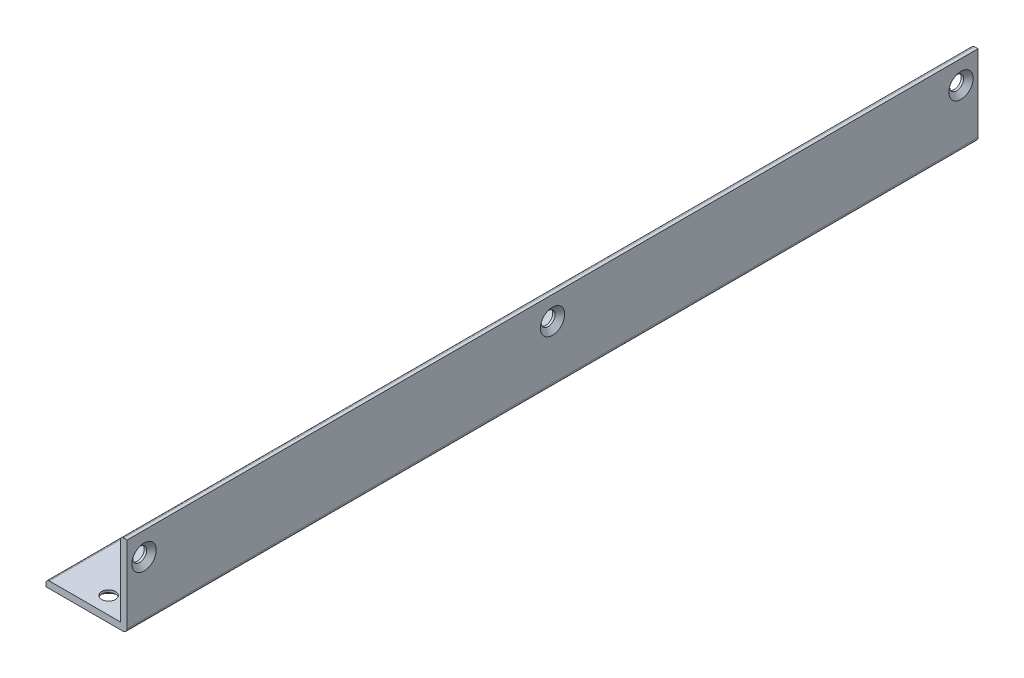
SolidWorks part; units mm, degrees
material "6061-T6 (SS)"
ref_plane "Front Plane" through (0, 0, 0) normal (0, 0, 1) x (1, 0, 0)
ref_plane "Top Plane" through (0, 0, 0) normal (0, 1, 0) x (1, 0, 0)
ref_plane "Right Plane" through (0, 0, 0) normal (1, 0, 0) x (0, 0, -1)
sketch "Sketch2" plane through (0, 0, 0) normal (0, 0, 1) x (1, 0, 0)
  line L0 (-9.525, 0) -> (9.525, 0)
  line L1 (9.525, 0) -> (9.525, 19.05)
  line L2 (9.525, 19.05) -> (7.9375, 19.05) construction
  line L3 (7.9375, 18.2563) -> (7.9375, 2.3812)
  line L4 (7.1438, 1.5875) -> (-8.7313, 1.5875)
  line L5 (-9.525, 0) -> (-9.525, 1.5875) construction
  line L6 (8.7313, 19.05) -> (9.525, 19.05)
  line L7 (-9.525, 0.7937) -> (-9.525, 0)
  arc A0 (7.9375, 18.2563) -> (8.7313, 19.05) centre (8.7313, 18.2563) cw
  arc A1 (-9.525, 0.7937) -> (-8.7313, 1.5875) centre (-8.7313, 0.7937) cw
  arc A2 (7.9375, 2.3812) -> (7.1438, 1.5875) centre (7.1438, 2.3812) cw
  dimension "Vert" = 19.05
  dimension "Horz" = 19.05
  dimension "Thickness" = 1.5875
extrude "Boss-Extrude1" add sketch "Sketch2" along normal mid plane 200
ref_plane "Contact Plane 1" through (0, 1.5875, 0) normal (0, 1, 0) x (1, 0, 0)
ref_plane "Contact Plane 2" through (7.9375, 0, 0) normal (-1, 0, 0) x (0, 0, 1)
sketch "Sketch6" plane through (0, 0, 0) normal (0, -1, 0) x (1, 0, 0)
  line L0 (9.525, 96) -> (1.185, 96) construction
  line L1 (9.525, 100) -> (9.525, -100) construction
  line L2 (-9.525, 100) -> (9.525, 100) construction
  line L3 (-9.525, -100) -> (9.525, -100) construction
  point P7 (1.185, 96)
  point P11 (0.275, -96)
  dimension "D1" = 4
  dimension "D2" = 8.34
  dimension "D3" = 4
  dimension "D4" = 9.25
hole_wizard "CSK for #4 Flat Head Machine Screw (100)1" positions "Sketch7" profile "Sketch8" countersink size "#4" standard "ANSI Inch" end condition through all
sketch "Sketch7" plane through (0, 0, 0) normal (0, -1, 0) x (-1, 0, 0)
  point P0 (-1.185, -96)
  point P3 (-0.275, 96)
sketch "Sketch8" plane through (1.185, 0, 96) normal (1, 0, 0) x (0, 0, -1)
  line L0 (0, 0) -> (0, 19.05)
  line L1 (0, 19.05) -> (1.6319, 19.05)
  line L2 (1.6319, 19.05) -> (1.6319, 1.0284)
  line L3 (1.6319, 1.0284) -> (2.8575, 0)
  line L5 (2.8575, 0) -> (0, 0)
  line L6 (-1.6319, 1.0284) -> (-2.8575, 0) construction
  line L11 (0, -6.35) -> (0, 107.95) construction
  dimension "Thru Hole Dia." = 3.2639
  dimension "Thru Hole Depth" = 19.05
  dimension "Near C'Sink Dia." = 5.715
  dimension "Near C'Sink Angle" = 100
sketch "Sketch9" plane through (9.525, 0, 0) normal (1, 0, 0) x (0, 0, -1)
  line L0 (-96, 0) -> (-96, 13.5875) construction
  line L1 (0, 0) -> (0, 19.05) construction
  line L2 (-100, 0) -> (100, 0) construction
  line L3 (-100, 19.05) -> (100, 19.05) construction
  point P4 (-96, 13.5875)
  point P10 (96, 13.5875)
  dimension "D1" = 13.5875
hole_wizard "CSK for #4 Flat Head Machine Screw (100)2" positions "Sketch10" profile "Sketch11" countersink size "#4" standard "ANSI Inch" end condition through all
sketch "Sketch10" plane through (9.525, 0, 0) normal (1, 0, 0) x (0, 0, -1)
  point P0 (-96, 13.5875)
  point P3 (96, 13.5875)
sketch "Sketch11" plane through (9.525, 13.5875, 96) normal (0, 1, 0) x (0, 0, -1)
  line L0 (0, 0) -> (0, 19.05)
  line L1 (0, 19.05) -> (1.6319, 19.05)
  line L2 (1.6319, 19.05) -> (1.6319, 1.0284)
  line L3 (1.6319, 1.0284) -> (2.8575, 0)
  line L5 (2.8575, 0) -> (0, 0)
  line L6 (-1.6319, 1.0284) -> (-2.8575, 0) construction
  line L11 (0, -6.35) -> (0, 107.95) construction
  dimension "Thru Hole Dia." = 3.2639
  dimension "Thru Hole Depth" = 19.05
  dimension "Near C'Sink Dia." = 5.715
  dimension "Near C'Sink Angle" = 100
fillet "Fillet1" radius 1 1 edges at (9.525, 0, 0)
sketch "Sketch12" plane through (0, 0, 0) normal (0, -1, 0) x (1, 0, 0)
  line L0 (0.275, -96) -> (0.275, -100) construction
  line L2 (-9.525, -100) -> (8.525, -100) construction
  line L3 (0.275, -100) -> (0.275, 0) construction
  point P8 (0.275, 0)
  dimension "D1" = 100
hole_wizard "CSK for #4 Flat Head Machine Screw (100)3" positions "Sketch15" profile "Sketch16" countersink size "#4" standard "ANSI Inch" end condition through all
sketch "Sketch15" plane through (0, 0, 0) normal (0, -1, 0) x (-1, 0, 0)
  point P0 (-0.275, 0)
sketch "Sketch16" plane through (0.275, 0, 0) normal (1, 0, 0) x (0, 0, -1)
  line L0 (0, 0) -> (0, 19.05)
  line L1 (0, 19.05) -> (1.6319, 19.05)
  line L2 (1.6319, 19.05) -> (1.6319, 1.0284)
  line L3 (1.6319, 1.0284) -> (2.8575, 0)
  line L5 (2.8575, 0) -> (0, 0)
  line L6 (-1.6319, 1.0284) -> (-2.8575, 0) construction
  line L11 (0, -6.35) -> (0, 107.95) construction
  dimension "Thru Hole Dia." = 3.2639
  dimension "Thru Hole Depth" = 19.05
  dimension "Near C'Sink Dia." = 5.715
  dimension "Near C'Sink Angle" = 100
sketch "Sketch17" plane through (9.525, 0, 0) normal (1, 0, 0) x (0, 0, -1)
  line L0 (96, 13.5875) -> (100, 13.5875) construction
  line L1 (100, 1) -> (100, 19.05) construction
  line L2 (100, 13.5875) -> (0, 13.5875) construction
  point P7 (0, 13.5875)
  dimension "D1" = 100
hole_wizard "CSK for #4 Flat Head Machine Screw (100)4" positions "Sketch18" profile "Sketch19" countersink size "#4" standard "ANSI Inch" end condition through all
sketch "Sketch18" plane through (9.525, 0, 0) normal (1, 0, 0) x (0, 0, -1)
  point P0 (0, 13.5875)
sketch "Sketch19" plane through (9.525, 13.5875, 0) normal (0, 1, 0) x (0, 0, -1)
  line L0 (0, 0) -> (0, 19.05)
  line L1 (0, 19.05) -> (1.6319, 19.05)
  line L2 (1.6319, 19.05) -> (1.6319, 1.0284)
  line L3 (1.6319, 1.0284) -> (2.8575, 0)
  line L5 (2.8575, 0) -> (0, 0)
  line L6 (-1.6319, 1.0284) -> (-2.8575, 0) construction
  line L11 (0, -6.35) -> (0, 107.95) construction
  dimension "Thru Hole Dia." = 3.2639
  dimension "Thru Hole Depth" = 19.05
  dimension "Near C'Sink Dia." = 5.715
  dimension "Near C'Sink Angle" = 100
sketch "Sketch20" [suppressed] plane through (0, 0, 0) normal (0, -1, 0) x (1, 0, 0)
  line L0 (0.275, -50) -> (0.275, 50) construction
  point P4 (0.275, 50)
  dimension "D1" = 100
hole_wizard "CSK for #4 Flat Head Machine Screw (100)5" [suppressed] positions "Sketch21" profile "Sketch22" countersink size "#4" standard "ANSI Inch"
sketch "Sketch21" plane through (0, 0, 0) normal (0, -1, 0) x (-1, 0, 0)
  point P0 (-0.275, -50)
sketch "Sketch22" plane through (0.275, 0, 50) normal (1, 0, 0) x (0, 0, -1)
  line L0 (0, 0) -> (0, 6.6706)
  line L1 (0, 6.6706) -> (1.6319, 5.69)
  line L2 (1.6319, 5.69) -> (1.6319, 1.0284)
  line L3 (1.6319, 1.0284) -> (2.8575, 0)
  line L5 (2.8575, 0) -> (0, 0)
  line L6 (-1.6319, 1.0284) -> (-2.8575, 0) construction
  line L10 (0, 6.6706) -> (-1.632, 5.69) construction
  line L11 (0, -6.35) -> (0, 107.95) construction
  dimension "Hole Dia." = 3.2639
  dimension "Hole Depth" = 5.69
  dimension "Near C'Sink Dia." = 5.715
  dimension "Near C'Sink Angle" = 100
  dimension "Drill Angle" = 118
sketch "Sketch23" plane through (9.525, 0, 0) normal (1, 0, 0) x (0, 0, -1)
  line L0 (0, 13.5875) -> (-100, 13.5875) construction
  point P4 (-100, 13.5875)
  dimension "D1" = 100
hole_wizard "CSK for #4 Flat Head Machine Screw (100)6" [suppressed] positions "Sketch24" profile "Sketch25" countersink size "#4" standard "ANSI Inch"
sketch "Sketch24" plane through (9.525, 0, 0) normal (1, 0, 0) x (0, 0, -1)
  point P0 (-50, 13.5875)
sketch "Sketch25" plane through (9.525, 13.5875, 50) normal (0, 1, 0) x (0, 0, -1)
  line L0 (0, 0) -> (0, 6.6706)
  line L1 (0, 6.6706) -> (1.6319, 5.69)
  line L2 (1.6319, 5.69) -> (1.6319, 1.0284)
  line L3 (1.6319, 1.0284) -> (2.8575, 0)
  line L5 (2.8575, 0) -> (0, 0)
  line L6 (-1.6319, 1.0284) -> (-2.8575, 0) construction
  line L10 (0, 6.6706) -> (-1.6319, 5.69) construction
  line L11 (0, -6.35) -> (0, 107.95) construction
  dimension "Hole Dia." = 3.2639
  dimension "Hole Depth" = 5.69
  dimension "Near C'Sink Dia." = 5.715
  dimension "Near C'Sink Angle" = 100
  dimension "Drill Angle" = 118
sketch "Sketch26" plane through (0, 0, 100) normal (0, 0, 1) x (1, 0, 0)
  line L0 (2.9375, 1.5875) -> (7.9375, 1.5875)
  line L1 (7.1438, 1.5875) -> (-8.7313, 1.5875) construction
  line L3 (7.9375, 18.2563) -> (7.9375, 2.3812) construction
  line L4 (7.9375, 6.5875) -> (7.9375, 1.5875)
  line L6 (2.9375, 1.5875) -> (7.9375, 6.5875)
  dimension "D1" = 5
  dimension "D2" = 5
extrude "Cut-Extrude1" cut sketch "Sketch26" against normal blind 25
ref_plane "Plane1" through (0, 0, 0) normal (0, 0, 1) x (1, 0, 0)
mirror "Mirror1" about plane through (0, 0, 0) normal (0, 0, 1) of "Cut-Extrude1"
